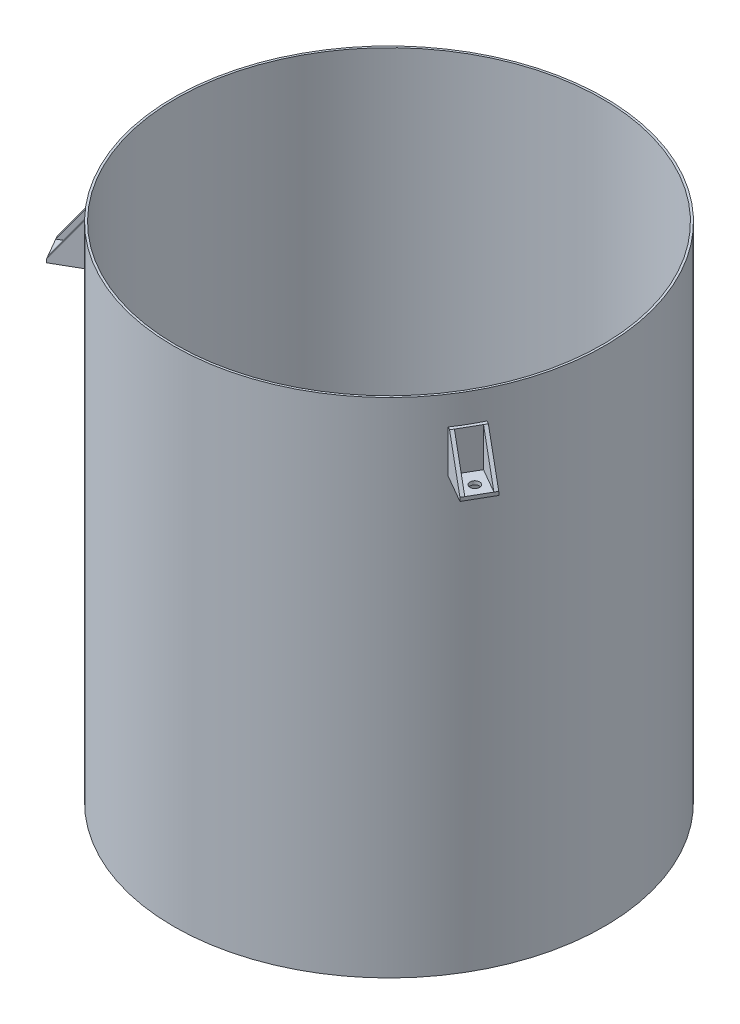
SolidWorks part; units mm, degrees
ref_plane "Front Plane" through (0, 0, 0) normal (0, 0, 1) x (1, 0, 0)
ref_plane "Top Plane" through (0, 0, 0) normal (0, 1, 0) x (1, 0, 0)
ref_plane "Right Plane" through (0, 0, 0) normal (1, 0, 0) x (0, 0, -1)
sketch "Sketch1" plane through (0, 0, 0) normal (0, 1, 0) x (1, 0, 0)
  circle A0 centre (0, 0) radius 300
  circle A1 centre (0, 0) radius 303
  dimension "D1" = 600
  dimension "D2" = 3
extrude "Boss-Extrude1" add sketch "Sketch1" along normal blind 707.4
sketch "Sketch3" plane through (0, 0, 0) normal (1, 0, 0) x (0, 0, -1)
  line L0 (293.5293, 0) -> (303, 0)
  line L1 (0, 0) -> (0, -50) construction
  line L2 (0, -47) -> (0, -50)
  line L3 (-293.5293, 0) -> (-303, 0)
  line L4 (293.5293, 0) -> (0, -47)
  line L5 (303, 0) -> (0, -50)
  arc A4 (283.6078, -3.2) -> (293.5293, 0) centre (0, 893.09) ccw
  dimension "D1" = 50
revolve "Revolve8" add sketch "Sketch3" angle 360 about L1
ref_plane "Plane1" through (0, 607.4, 0) normal (0, 1, 0) x (1, 0, 0)
sketch "Sketch7" plane through (0, 607.4, 0) normal (0, 1, 0) x (1, 0, 0)
  line L0 (0, 0) -> (0, 633.9048) construction
  line L1 (0, 307.3392) -> (20, 307.3392)
  line L2 (20, 307.3392) -> (20, 302.3392)
  line L5 (0, 307.3392) -> (-20, 307.3392)
  line L6 (-20, 307.3392) -> (-20, 302.3392)
  arc A0 (20, 302.3392) -> (-20, 302.3392) centre (0, 0) ccw
  dimension "D1" = 20
  dimension "D4" = 5
  dimension "D2" = 20
extrude "Boss-Extrude2" add sketch "Sketch7" along normal blind 60
ref_plane "Plane2" through (0, 0, -304) normal (0, 0, 1) x (1, 0, 0)
sketch "Sketch8" plane through (0, 0, -307.3392) normal (0, 0, -1) x (-1, 0, 0)
  line L0 (-20, 667.4) -> (-20, 607.4)
  line L1 (-20, 667.4) -> (-20, 607.4) construction
  line L2 (-20, 667.4) -> (-20, 607.4) construction
  line L3 (-20, 607.4) -> (20, 607.4)
  line L4 (20, 607.4) -> (20, 667.4)
  line L5 (20, 667.4) -> (15, 667.4)
  line L6 (-20, 667.4) -> (20, 667.4) construction
  line L7 (15, 667.4) -> (15, 612.4)
  line L8 (15, 612.4) -> (-15, 612.4)
  line L9 (-15, 612.4) -> (-15, 667.4)
  line L10 (20, 667.4) -> (-20, 667.4) construction
  line L11 (-15, 667.4) -> (-20, 667.4)
  dimension "D1" = 5
  dimension "D2" = 5
  dimension "D3" = 5
extrude "Boss-Extrude3" add sketch "Sketch8" along normal blind 40
sketch "Sketch11" plane through (20, 0, 0) normal (1, 0, 0) x (0, 0, -1)
  line L0 (307.3392, 667.4) -> (347.3392, 612.4)
  line L1 (347.3392, 612.4) -> (347.3392, 667.4)
  line L2 (347.3392, 667.4) -> (307.3392, 667.4)
extrude "Cut-Extrude1" cut sketch "Sketch11" against normal blind 40
pattern_circular "CirPattern1" count 3 over 360 about axis through (0, 0, 0) along (0, 1, 0) of "Boss-Extrude2", "Cut-Extrude1", "Boss-Extrude3"
sketch "Sketch12" plane through (0, 612.4, 0) normal (0, 1, 0) x (1, 0, 0)
  line L0 (0, 0) -> (0, 537.7877) construction
  line L1 (0, 0) -> (477.2143, -275.5198) construction
  line L2 (0, 0) -> (-454.6884, -262.5145) construction
  circle A0 centre (0, 0) radius 330 construction
  circle A1 centre (0, 330) radius 6.75
  circle A2 centre (285.7884, -165) radius 6.75
  circle A3 centre (-285.7884, -165) radius 6.75
  dimension "D1" = 660
  dimension "D4" = 13.5
  dimension "D5" = 13.5
  dimension "D6" = 13.5
  dimension "D2" = 120
  dimension "D3" = 120
extrude "Cut-Extrude2" cut sketch "Sketch12" against normal blind 40
ref_plane "Plane8" through (0, -50, 0) normal (0, 1, 0) x (1, 0, 0)
sketch "Sketch13" plane through (0, -50, 0) normal (0, 1, 0) x (1, 0, 0)
  circle A0 centre (0, 0) radius 25
  circle A1 centre (0, 0) radius 28
  dimension "D2" = 50
  dimension "D1" = 3
extrude "Boss-Extrude5" add sketch "Sketch13" against normal blind 50 and the other way up to next
sketch "Sketch14" plane through (0, -50, 0) normal (0, 1, 0) x (1, 0, 0)
  circle A0 centre (0, 0) radius 25
  dimension "D1" = 50
sketch "Sketch15" plane through (0, -50, 0) normal (0, 1, 0) x (1, 0, 0)
  circle A0 centre (0, 0) radius 25
  dimension "D1" = 50
extrude "Cut-Extrude4" cut sketch "Sketch15" against normal blind 60 and the other way blind 10
